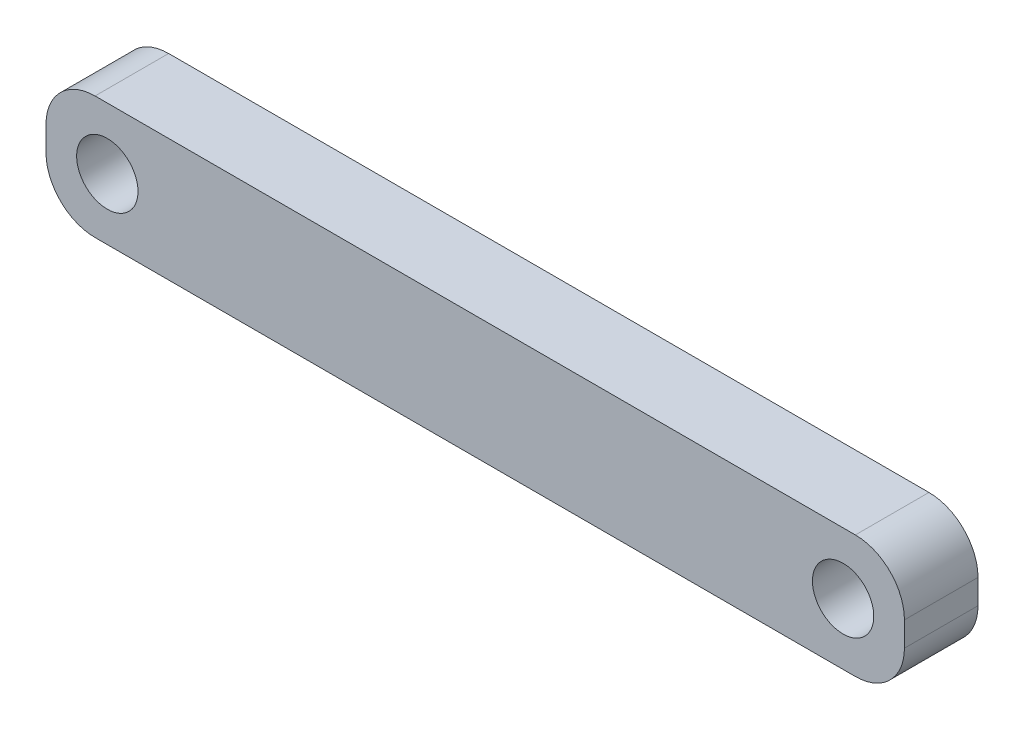
SolidWorks part; units mm, degrees
ref_plane "Front Plane" through (0, 0, 0) normal (0, 0, 1) x (1, 0, 0)
ref_plane "Top Plane" through (0, 0, 0) normal (0, 1, 0) x (1, 0, 0)
ref_plane "Right Plane" through (0, 0, 0) normal (1, 0, 0) x (0, 0, -1)
sketch "Sketch1" plane through (0, 0, 0) normal (0, 0, 1) x (1, 0, 0)
  line L0 (-48.9577, 0) -> (39.3424, 0) construction
  line L1 (-31, 5) -> (31, 5)
  line L2 (-35, 1) -> (-35, -1)
  line L3 (-31, -5) -> (31, -5)
  line L4 (35, 1) -> (35, -1)
  line L5 (-35, 5) -> (35, -5) construction
  line L6 (-35, -5) -> (35, 5) construction
  line L8 (0, 29.2082) -> (0, -27.0284) construction
  arc A0 (31, -5) -> (35, -1) centre (31, -1) ccw
  arc A1 (31, 5) -> (35, 1) centre (31, 1) cw
  arc A2 (-35, -1) -> (-31, -5) centre (-31, -1) ccw
  arc A3 (-31, 5) -> (-35, 1) centre (-31, 1) ccw
  circle A4 centre (-30, 0) radius 2.5
  circle A5 centre (30, 0) radius 2.5
  point P0 (0, 0)
  dimension "D3" = 4
  dimension "D4" = 5
  dimension "D1" = 70
  dimension "D2" = 10
extrude "Boss-Extrude1" add sketch "Sketch1" along normal blind 6
